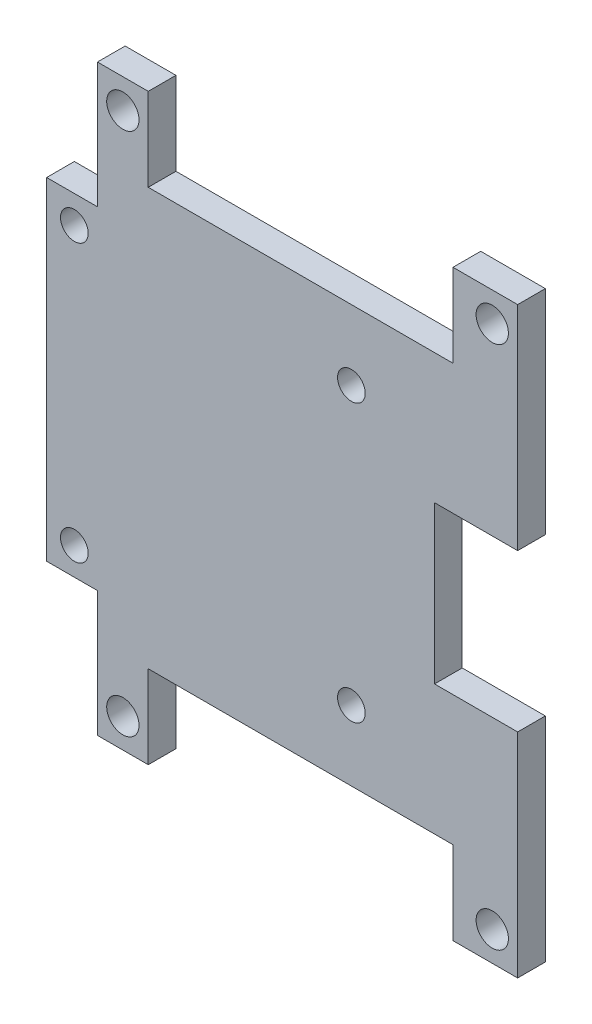
SolidWorks part; units mm, degrees
ref_plane "Front" through (0, 0, 0) normal (0, 0, 1) x (1, 0, 0)
ref_plane "Top" through (0, 0, 0) normal (0, 1, 0) x (1, 0, 0)
ref_plane "Right" through (0, 0, 0) normal (1, 0, 0) x (0, 0, -1)
sketch "Sketch1" plane through (0, 0, 0) normal (0, 0, 1) x (1, 0, 0)
  line L1 (-22.75, -31.575) -> (22.75, -31.575)
  line L2 (-22.75, -31.575) -> (-22.75, 31.575)
  line L3 (-22.75, 31.575) -> (22.75, 31.575)
  line L4 (22.75, -31.575) -> (22.75, 31.575)
  line L5 (-22.75, -31.575) -> (22.75, 31.575) construction
  line L6 (-22.75, 31.575) -> (22.75, -31.575) construction
  point P0 (0, 0)
  dimension "D1" = 63.15
  dimension "D2" = 45.5
extrude "Boss-Extrude1" add sketch "Sketch1" along normal blind 3
sketch "Sketch2" plane through (0, 0, 3) normal (0, 0, 1) x (1, 0, 0)
  line L0 (22.75, -31.575) -> (22.75, 31.575) construction
  line L1 (-22.75, -31.575) -> (22.75, -31.575) construction
  line L2 (0, 0) -> (-22.75, 0) construction
  line L3 (-22.75, 31.575) -> (-22.75, -31.575) construction
  line L4 (0, 0) -> (0, 31.575) construction
  line L5 (22.75, 31.575) -> (-22.75, 31.575) construction
  circle A0 centre (20, -28.395) radius 1.75
  circle A1 centre (20, 28.395) radius 1.75
  circle A2 centre (-20, 28.395) radius 1.75
  circle A3 centre (-20, -28.395) radius 1.75
  dimension "D3" = 3.5
  dimension "D1" = 2.75
  dimension "D2" = 3.18
extrude "Cut-Extrude1" cut sketch "Sketch2" against normal blind 3
sketch "Sketch3" plane through (0, 0, 3) normal (0, 0, 1) x (1, 0, 0)
  line L0 (15.75, 31.575) -> (15.75, 22.575)
  line L1 (22.75, 31.575) -> (-22.75, 31.575) construction
  line L2 (15.75, 22.575) -> (-17.25, 22.575)
  line L3 (-17.25, 22.575) -> (-17.25, 31.575)
  line L4 (-22.75, 31.575) -> (-22.75, -31.575) construction
  line L5 (22.75, -31.575) -> (22.75, 31.575) construction
  line L6 (-22.75, 0) -> (0, 0) construction
  line L7 (-17.25, 31.575) -> (15.75, 31.575)
  line L8 (-17.25, -31.575) -> (15.75, -31.575)
  line L9 (-17.25, -22.575) -> (-17.25, -31.575)
  line L10 (15.75, -22.575) -> (-17.25, -22.575)
  line L11 (15.75, -31.575) -> (15.75, -22.575)
  dimension "D1" = 5.5
  dimension "D2" = 7
  dimension "D3" = 90
  dimension "D4" = 9
extrude "Cut-Extrude2" cut sketch "Sketch3" against normal blind 3
sketch "Sketch4" plane through (0, 0, 3) normal (0, 0, 1) x (1, 0, 0)
  line L0 (-22.75, -17.995) -> (-28.25, -17.995)
  line L1 (-22.75, 31.575) -> (-22.75, -31.575) construction
  line L2 (-28.25, -17.995) -> (-28.25, 17.995)
  line L3 (-28.25, 17.995) -> (-22.75, 17.995)
  line L4 (-17.25, 31.575) -> (-22.75, 31.575) construction
  line L5 (-22.75, -31.575) -> (-17.25, -31.575) construction
  line L6 (-22.75, -17.995) -> (-22.75, 17.995)
  dimension "D1" = 5.5
  dimension "D2" = 13.58
  dimension "D3" = 13.58
extrude "Boss-Extrude2" add sketch "Sketch4" against normal blind 3
sketch "Sketch5" plane through (0, 0, 0) normal (0, 0, -1) x (-1, 0, 0)
  circle A0 centre (-4.75, 15) radius 1.5
  circle A1 centre (25.25, 15) radius 1.5
  circle A2 centre (25.25, -15) radius 1.5
  circle A3 centre (-4.75, -15) radius 1.5
extrude "Cut-Extrude3" cut sketch "Sketch5" against normal blind 3
sketch "Sketch6" plane through (0, 0, 0) normal (0, 0, -1) x (-1, 0, 0)
  line L0 (-22.75, 0) -> (28.25, 0) construction
  line L1 (-22.75, -31.575) -> (-22.75, 31.575) construction
  line L2 (28.25, 17.995) -> (28.25, -17.995) construction
  line L3 (-22.75, 0) -> (-22.75, -8.5)
  line L4 (-22.75, -8.5) -> (-13.75, -8.5)
  line L5 (-13.75, -8.5) -> (-13.75, 8.5)
  line L6 (-13.75, 8.5) -> (-22.75, 8.5)
  line L7 (-22.75, 0) -> (-22.75, 8.5)
  dimension "D1" = 8.5
  dimension "D2" = 8.5
  dimension "D3" = 9
extrude "Cut-Extrude4" cut sketch "Sketch6" against normal blind 10
